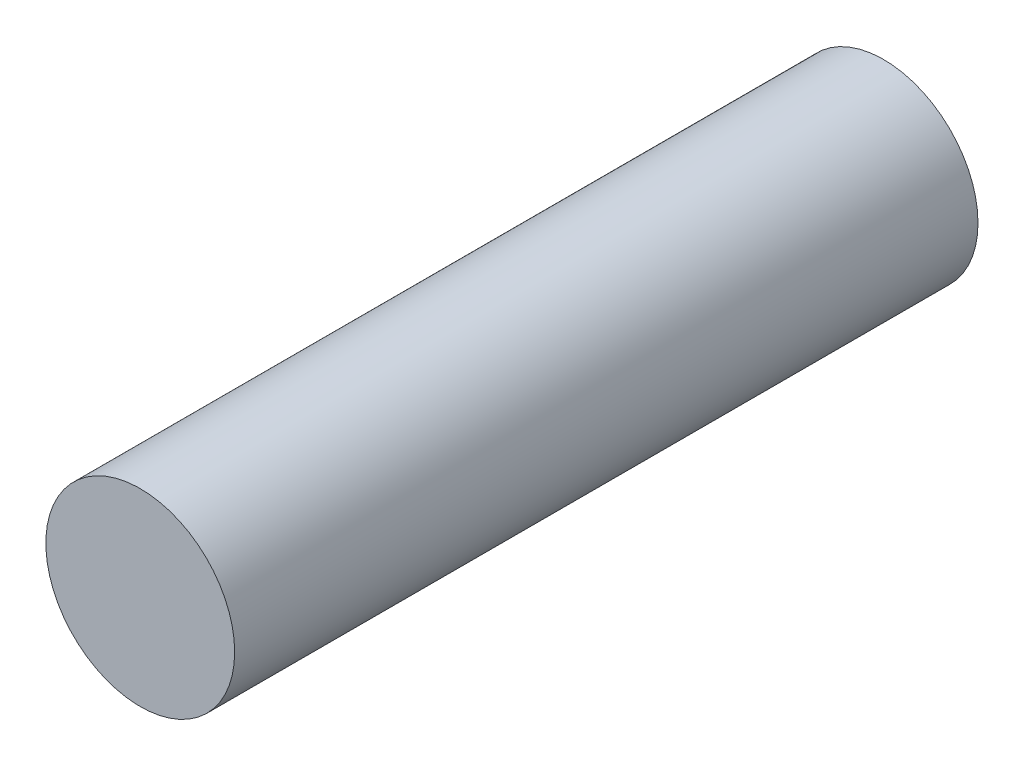
SolidWorks part; units mm, degrees
ref_plane "Front Plane" through (0, 0, 0) normal (0, 0, 1) x (1, 0, 0)
ref_plane "Top Plane" through (0, 0, 0) normal (0, 1, 0) x (1, 0, 0)
ref_plane "Right Plane" through (0, 0, 0) normal (1, 0, 0) x (0, 0, -1)
sketch "Sketch1" plane through (0, 0, 0) normal (0, 0, 1) x (1, 0, 0)
  circle A0 centre (0, 0) radius 76.2
  dimension "D1" = 152.4
extrude "Boss-Extrude1" add sketch "Sketch1" along normal blind 600
